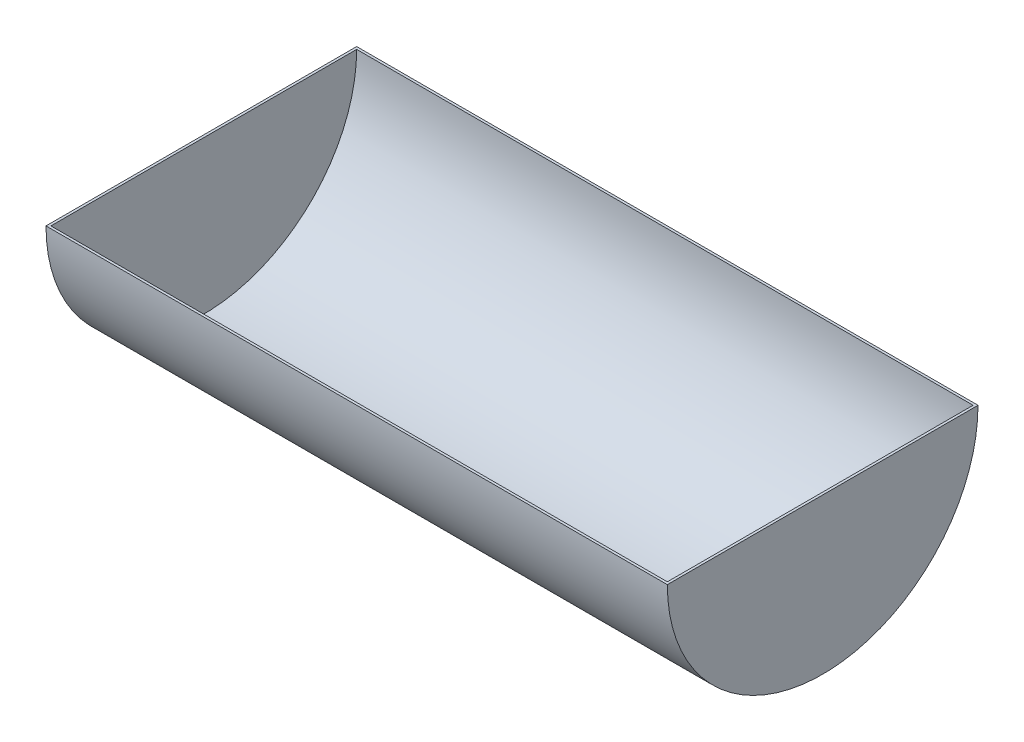
SolidWorks part; units mm, degrees
material "Galvanized Steel"
ref_plane "Front Plane" through (0, 0, 0) normal (0, 0, 1) x (1, 0, 0)
ref_plane "Top Plane" through (0, 0, 0) normal (0, 1, 0) x (1, 0, 0)
ref_plane "Right Plane" through (0, 0, 0) normal (1, 0, 0) x (0, 0, -1)
sketch "Sketch1" plane through (0, 0, 0) normal (1, 0, 0) x (0, 0, -1)
  line L0 (0, 0) -> (125, 0) construction
  line L1 (127, 0) -> (125, 0)
  line L2 (0, 0) -> (-125, 0) construction
  line L3 (-127, 0) -> (-125, 0)
  arc A0 (-127, 0) -> (127, 0) centre (0, 0) ccw
  arc A1 (-125, 0) -> (125, 0) centre (0, 0) ccw
  circle A3 centre (0, 0) radius 125 construction
  circle A4 centre (0, 0) radius 127 construction
  point P4 (121.4507, 37.1312)
  point P9 (125, 0)
  dimension "D1" = 254
  dimension "D2" = 2
extrude "Boss-Extrude1" add sketch "Sketch1" along normal blind 508
sketch "Sketch2" plane through (508, 0, 0) normal (1, 0, 0) x (0, 0, -1)
  line L0 (-125, 0) -> (125, 0)
  arc A0 (-125, 0) -> (125, 0) centre (0, 0) ccw construction
  arc A1 (-125, 0) -> (125, 0) centre (0, 0) ccw
extrude "Boss-Extrude2" add sketch "Sketch2" against normal blind 2
pattern_linear "LPattern1" count 2 spacing 506 along (-1, 0, 0) of "Boss-Extrude2"
